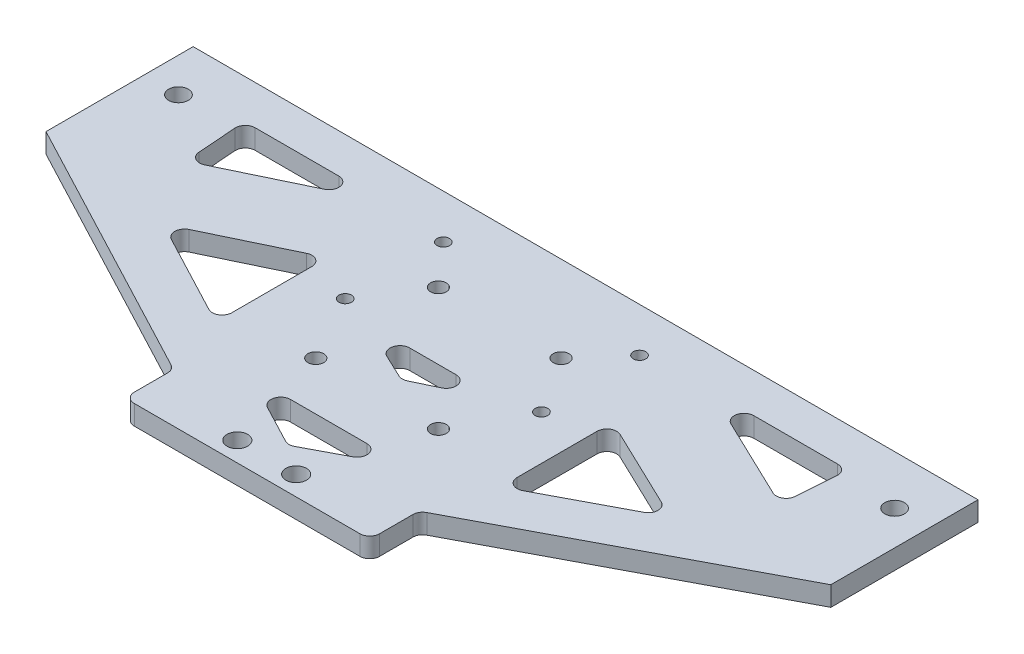
SolidWorks part; units mm, degrees
material "Thornel Mat VMA"
ref_plane "Front" through (0, 0, 0) normal (0, 0, 1) x (1, 0, 0)
ref_plane "Top" through (0, 0, 0) normal (0, 1, 0) x (1, 0, 0)
ref_plane "Right" through (0, 0, 0) normal (1, 0, 0) x (0, 0, -1)
sketch "草图1" plane through (0, 0, 0) normal (0, 1, 0) x (1, 0, 0)
  line L0 (0, 40.0348) -> (0, 0) construction
  line L1 (25, 0) -> (-25, 0)
  line L2 (-25, 0) -> (-80, 29)
  line L3 (-80, 29) -> (-80, 59)
  line L4 (-80, 59) -> (80, 59)
  line L5 (80, 29) -> (80, 59)
  line L6 (25, 0) -> (80, 29)
  point P9 (0, 59)
  dimension "D1" = 59
  dimension "D2" = 80
  dimension "D3" = 25
  dimension "D4" = 30
extrude "凸台-拉伸1" add sketch "草图1" along normal blind 4
sketch "草图2" plane through (0, 4, 0) normal (0, 1, 0) x (1, 0, 0)
  line L0 (0, 0) -> (0, 59) construction
  line L1 (80, 59) -> (-80, 59) construction
  line L2 (-12.5, 41.5) -> (-12.5, 16.5) construction
  line L3 (-12.5, 29) -> (12.5, 29) construction
  line L4 (12.5, 41.5) -> (12.5, 16.5) construction
  circle A0 centre (-12.5, 41.5) radius 1.6
  circle A3 centre (12.5, 41.5) radius 1.6
  circle A4 centre (-12.5, 16.5) radius 1.6
  circle A5 centre (12.5, 16.5) radius 1.6
  point P14 (0, 29)
  dimension "D1" = 3.2
  dimension "D2" = 25
  dimension "D4" = 17.5
  dimension "D3" = 12.5
extrude "切除-拉伸1" cut sketch "草图2" against normal through all
sketch "草图3" plane through (0, 4, 0) normal (0, 1, 0) x (1, 0, 0)
  line L0 (-80, 59) -> (-80, 29) construction
  line L1 (80, 59) -> (-80, 59) construction
  line L23 (-25, 0) -> (25, 0) construction
  line L24 (-66, 51.4654) -> (-66, 27.9182)
  line L25 (-65.4092, 27.0057) -> (-27.5283, 10.0199)
  line L26 (-26.3885, 11.6151) -> (-64.2694, 52.1482)
  line L27 (-56.7306, 52.8689) -> (-35.4528, 30.1014)
  line L28 (-33.7222, 30.7842) -> (-33.7222, 50.1473)
  line L29 (-34.5642, 51.1347) -> (-55.842, 54.5392)
  line L32 (-22.9874, 9.4403) -> (-26.732, 36.0544)
  line L33 (-80, 29) -> (-25, 0) construction
  line L34 (-13.5, 37) -> (-13.5, 17) construction
  line L35 (-28.7222, 35.9151) -> (-28.7222, 11.1733)
  line L36 (-28.1694, 10.2789) -> (-24.4249, 8.4066)
  line L37 (-13.5, 37) -> (-12.5, 41.5) construction
  line L38 (-4.3247, 7.5552) -> (-22.7222, 7.5552) construction
  line L39 (0, 30) -> (0, 0) construction
  line L40 (4.3247, 7.5552) -> (22.7222, 7.5552) construction
  line L41 (7.5, 20.5) -> (7.5, 10.5) construction
  line L42 (28.1694, 10.2789) -> (24.4249, 8.4066)
  line L43 (28.7222, 35.9151) -> (28.7222, 11.1733)
  line L44 (22.9874, 9.4403) -> (26.732, 36.0544)
  line L45 (34.5642, 51.1347) -> (55.842, 54.5392)
  line L46 (33.7222, 30.7842) -> (33.7222, 50.1473)
  line L47 (56.7306, 52.8689) -> (35.4528, 30.1014)
  line L48 (26.3885, 11.6151) -> (64.2694, 52.1482)
  line L49 (65.4092, 27.0057) -> (27.5283, 10.0199)
  line L50 (66, 51.4654) -> (66, 27.9182)
  line L51 (-12.5, 16.5) -> (-13.5, 17) construction
  circle A0 centre (-73, 51) radius 2.6
  arc A1 (-24.4249, 8.4066) -> (-22.9874, 9.4403) centre (-23.9777, 9.301) ccw
  arc A2 (-28.7222, 11.1733) -> (-28.1694, 10.2789) centre (-27.7222, 11.1733) ccw
  arc A3 (-28.7222, 35.9151) -> (-26.732, 36.0544) centre (-27.7222, 35.9151) cw
  arc A4 (-33.7222, 50.1473) -> (-34.5642, 51.1347) centre (-34.7222, 50.1473) ccw
  arc A5 (-56.7306, 52.8689) -> (-55.842, 54.5392) centre (-56, 53.5517) cw
  arc A6 (-35.4528, 30.1014) -> (-33.7222, 30.7842) centre (-34.7222, 30.7842) ccw
  arc A7 (-26.3885, 11.6151) -> (-27.5283, 10.0199) centre (-27.1191, 10.9323) cw
  arc A8 (-66, 27.9182) -> (-65.4092, 27.0057) centre (-65, 27.9182) ccw
  arc A9 (-66, 51.4654) -> (-64.2694, 52.1482) centre (-65, 51.4654) cw
  arc A10 (66, 51.4654) -> (64.2694, 52.1482) centre (65, 51.4654) ccw
  arc A11 (66, 27.9182) -> (65.4092, 27.0057) centre (65, 27.9182) cw
  arc A12 (26.3885, 11.6151) -> (27.5283, 10.0199) centre (27.1191, 10.9323) ccw
  arc A13 (35.4528, 30.1014) -> (33.7222, 30.7842) centre (34.7222, 30.7842) cw
  arc A14 (56.7306, 52.8689) -> (55.842, 54.5392) centre (56, 53.5517) ccw
  arc A15 (33.7222, 50.1473) -> (34.5642, 51.1347) centre (34.7222, 50.1473) cw
  arc A16 (28.7222, 35.9151) -> (26.732, 36.0544) centre (27.7222, 35.9151) ccw
  arc A17 (28.7222, 11.1733) -> (28.1694, 10.2789) centre (27.7222, 11.1733) cw
  arc A18 (24.4249, 8.4066) -> (22.9874, 9.4403) centre (23.9777, 9.301) cw
  circle A19 centre (73, 51) radius 2.6
  circle A20 centre (-13.5, 17) radius 1.6
  circle A21 centre (-13.5, 37) radius 1.6
  circle A22 centre (13.5, 17) radius 1.6
  circle A23 centre (13.5, 37) radius 1.6
  point P24 (-28.7222, 10.5552)
  point P32 (-28.7222, 50.2)
  point P35 (-33.7222, 51)
  point P38 (-58.7222, 55)
  point P43 (-23, 7.9894)
  point P46 (-66, 27.2707)
  point P49 (-66, 54)
  point P86 (66, 54)
  point P87 (66, 27.2707)
  point P88 (23, 7.9894)
  point P89 (58.7222, 55)
  point P90 (33.7222, 51)
  point P91 (28.7222, 50.2)
  point P92 (28.7222, 10.5552)
  dimension "D1" = 5.2
  dimension "D2" = 7
  dimension "D3" = 8
  dimension "D15" = 1
  dimension "D16" = 3.2
  dimension "D17" = 27
  dimension "D18" = 17
  dimension "D20" = 3.2
  dimension "D4" = 7
  dimension "D5" = 5
  dimension "D6" = 5
  dimension "D7" = 8
  dimension "D8" = 6
  dimension "D9" = 4
  dimension "D10" = 8
  dimension "D11" = 2
  dimension "D12" = 5
  dimension "D13" = 25
  dimension "D14" = 6
  dimension "D19" = 20
extrude "切除-拉伸2" [suppressed] cut sketch "草图3" against normal through all
fillet "圆角1" [suppressed] radius 7
sketch "草图4" plane through (0, 4, 0) normal (0, 1, 0) x (1, 0, 0)
  line L0 (0, 0) -> (0, 67.0073) construction
  line L1 (80, 59) -> (-80, 59) construction
  circle A0 centre (20, 50) radius 1.275
  circle A2 centre (20, 30) radius 1.275
  circle A3 centre (-20, 30) radius 1.275
  circle A4 centre (-20, 50) radius 1.275
  dimension "D1" = 2.55
  dimension "D2" = 20
  dimension "D4" = 9
  dimension "D5" = 20
  dimension "D3" = 2
extrude "切除-拉伸3" cut sketch "草图4" against normal blind 10
sketch "草图6" plane through (0, 4, 0) normal (0, 1, 0) x (1, 0, 0)
  line L1 (-25, 0) -> (25, 0)
  line L2 (-25, 0) -> (-25, -10)
  line L3 (-25, -10) -> (25, -10)
  line L4 (25, 0) -> (25, -10)
  dimension "D1" = 50
  dimension "D2" = 10
extrude "凸台-拉伸2" add sketch "草图6" against normal up to surface (4 mm away) up to face at (-20, 0, -51.275)
sketch "草图7" plane through (0, 4, 0) normal (0, 1, 0) x (1, 0, 0)
  line L0 (0, 0) -> (0, -33.3189) construction
  line L1 (-25, -10) -> (25, -10) construction
  circle A0 centre (-6, -6) radius 2.1
  circle A1 centre (6, -6) radius 2.1
  dimension "D1" = 4.2
  dimension "D2" = 6
  dimension "D3" = 4
extrude "切除-拉伸4" cut sketch "草图7" against normal blind 10
sketch "草图8" plane through (0, 4, 0) normal (0, 1, 0) x (1, 0, 0)
  line L0 (-80, 59) -> (-80, 29) construction
  line L1 (80, 59) -> (-80, 59) construction
  line L2 (0, 0) -> (0, 67.9824) construction
  circle A0 centre (-73, 49) radius 2
  circle A1 centre (73, 49) radius 2
  dimension "D1" = 4
  dimension "D2" = 7
  dimension "D3" = 10
extrude "切除-拉伸5" cut sketch "草图8" against normal blind 10
sketch "草图9" plane through (0, 4, 0) normal (0, 1, 0) x (1, 0, 0)
  line L0 (0, 0) -> (0, 79.7791) construction
  line L1 (-13.6072, 27.8756) -> (13.6072, 27.8756)
  line L2 (-13.6072, 27.8756) -> (0, 21.4248)
  line L3 (-61.5112, 51) -> (-33.5112, 51)
  line L4 (-33.5112, 51) -> (-60.5648, 38.0345)
  line L5 (-60.5648, 38.0345) -> (-61.5112, 51)
  line L6 (-51.7088, 24.599) -> (-29.0798, 35.444)
  line L7 (-29.0798, 35.444) -> (-29.0798, 12.6673)
  line L8 (-29.0798, 12.6673) -> (-51.7088, 24.599)
  line L9 (29.0798, 12.6673) -> (51.7088, 24.599)
  line L10 (29.0798, 35.444) -> (29.0798, 12.6673)
  line L11 (51.7088, 24.599) -> (29.0798, 35.444)
  line L12 (60.5648, 38.0345) -> (61.5112, 51)
  line L13 (33.5112, 51) -> (60.5648, 38.0345)
  line L14 (61.5112, 51) -> (33.5112, 51)
  line L15 (13.6072, 27.8756) -> (0, 21.4248)
  line L16 (80, 59) -> (-80, 59) construction
  line L17 (-80, 29) -> (-25, 0) construction
  line L18 (-80, 59) -> (-80, 29) construction
  point P19 (0, 27.8756)
  dimension "D1" = 28
  dimension "D2" = 8
  dimension "D3" = 13
  dimension "D4" = 30
extrude "切除-拉伸6" cut sketch "草图9" against normal blind 10
sketch "草图10" plane through (0, 4, 0) normal (0, 1, 0) x (1, 0, 0)
  line L0 (0, 0) -> (0, -26.7425) construction
  line L1 (0, 0) -> (0, 25.9451) construction
  line L2 (-15.8628, 6.6366) -> (15.8628, 6.6366)
  line L3 (15.8628, 6.6366) -> (0, -1.7274)
  line L4 (25, 0) -> (80, 29) construction
  line L5 (-15.8628, 6.6366) -> (0, -1.7274)
  point P11 (0, 6.6366)
extrude "切除-拉伸7" cut sketch "草图10" against normal blind 10
fillet "圆角2" radius 2 22 edges at (-25, 2, 0) (-25, 2, 10) (25, 2, 10) (25, 2, 0) (-13.6072, 2, -27.8756) (13.6072, 2, -27.8756) (0, 2, -21.4248) (-51.7088, 2, -24.599) (-29.0798, 2, -35.444) (-29.0798, 2, -12.6673) (-61.5112, 2, -51) (-33.5112, 2, -51) (-60.5648, 2, -38.0345) (33.5112, 2, -51) (61.5112, 2, -51) (60.5648, 2, -38.0345) (29.0798, 2, -35.444) (51.7088, 2, -24.599) (0, 2, 1.7274) (-15.8628, 2, -6.6366) (15.8628, 2, -6.6366) (29.0798, 2, -12.6673)
